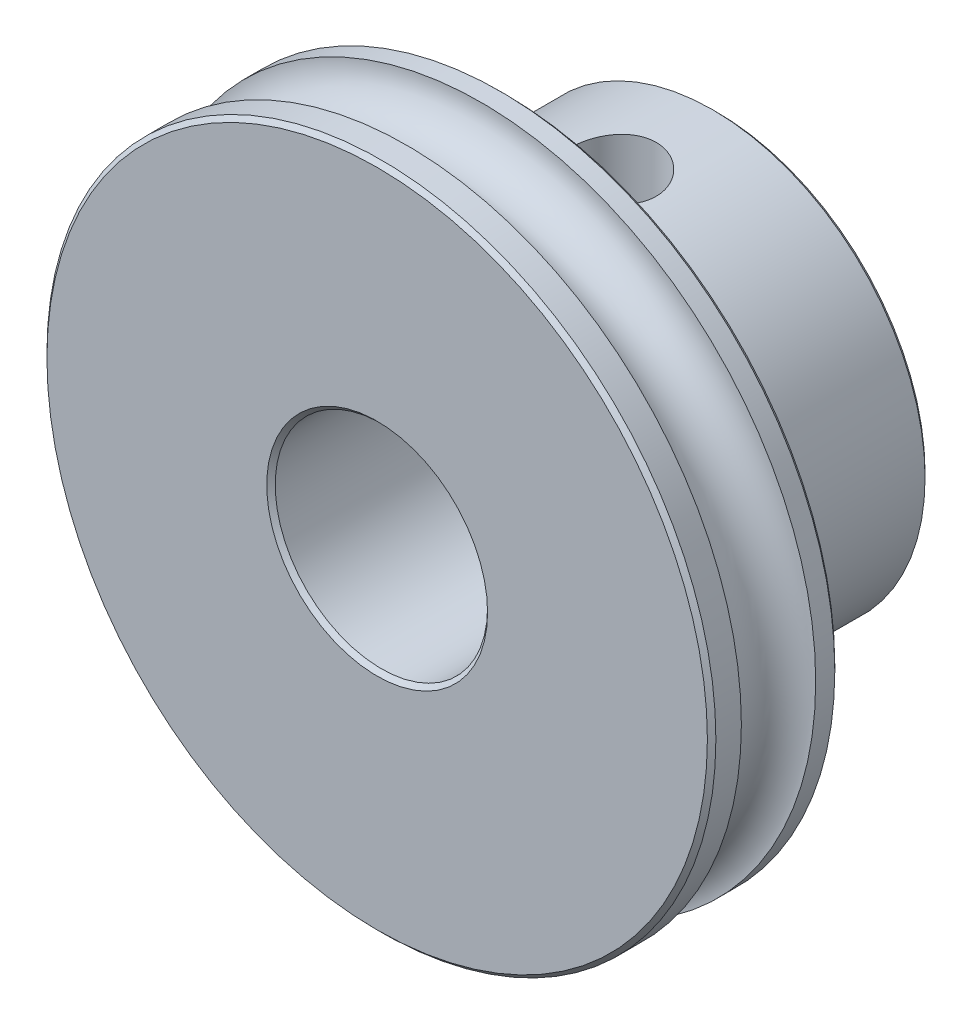
SolidWorks part; units mm, degrees
ref_plane "前视基准面" through (0, 0, 0) normal (0, 0, 1) x (1, 0, 0)
ref_plane "上视基准面" through (0, 0, 0) normal (0, 1, 0) x (1, 0, 0)
ref_plane "右视基准面" through (0, 0, 0) normal (1, 0, 0) x (0, 0, -1)
sketch "草图1" plane through (0, 0, 0) normal (1, 0, 0) x (0, 0, -1)
  line L0 (0, 0) -> (46.9269, 0) construction
  line L1 (0.8616, 5) -> (16.8616, 5)
  line L2 (0.8616, 15.75) -> (2.2616, 15.75)
  line L3 (5.7616, 15.75) -> (6.8616, 15.75)
  line L6 (16.8616, 10) -> (6.8616, 10)
  line L7 (6.8616, 15.75) -> (6.8616, 10)
  line L9 (16.8616, 10) -> (16.8616, 5)
  line L10 (0.8616, 15.75) -> (0.8616, 5)
  arc A0 (2.2616, 15.75) -> (5.7616, 15.75) centre (4.0116, 15.75) ccw
  dimension "D2" = 3.5
  dimension "D1" = 5
  dimension "D3" = 15.75
  dimension "D6" = 10
  dimension "D8" = 10
  dimension "D9" = 16
revolve "旋转1" add sketch "草图1" angle 360 about L0
hole_wizard "M4 螺纹孔1" positions "草图3" profile "草图2" tap size "M4" standard "GB"
sketch "草图3" plane through (0, 0, 0) normal (0, 1, 0) x (1, 0, 0)
  point P0 (0, 12)
sketch "草图2" plane through (0, 0, -12) normal (1, 0, 0) x (0, 0, -1)
  line L0 (0, 0) -> (0, 21.5149)
  line L1 (0, 21.5149) -> (2, 21.5149)
  line L2 (2, 21.5149) -> (2, 0)
  line L5 (2, 0) -> (0, 0)
  line L11 (0, -6.35) -> (0, 107.95) construction
  dimension "螺纹线主直径" = 4
  dimension "通孔螺纹孔钻头深度" = 21.5149
pattern_circular "阵列(圆周)1" count 2 every 120 about axis through (0, 0, 0) along (0, 0, 1) of "M4 螺纹孔1"
chamfer "倒角1" distance 0.2 angle 45 5 edges at (5, 0, -0.8616) (5, 0, -16.8616) (10, 0, -16.8616) (15.75, 0, -0.8616) (15.75, 0, -6.8616)
chamfer "倒角2" distance 0.5 angle 45 1 edges at (10, 0, -6.8616)
